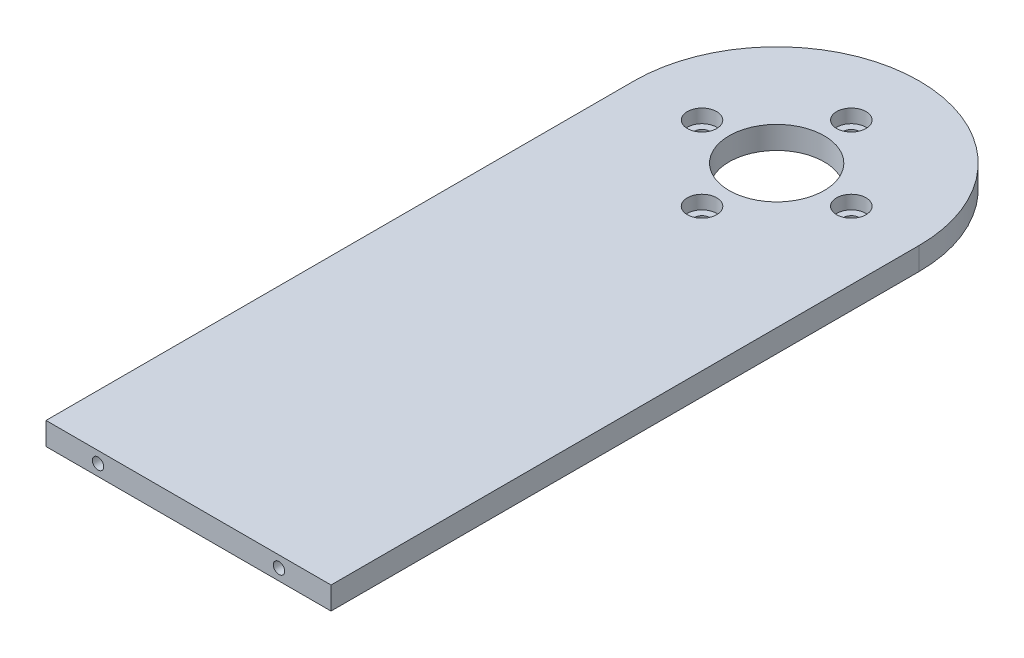
SolidWorks part; units mm, degrees
ref_plane "Front Plane" through (0, 0, 0) normal (0, 0, 1) x (1, 0, 0)
ref_plane "Top Plane" through (0, 0, 0) normal (0, 1, 0) x (1, 0, 0)
ref_plane "Right Plane" through (0, 0, 0) normal (1, 0, 0) x (0, 0, -1)
sketch "Sketch1" plane through (0, 0, 0) normal (0, 1, 0) x (1, 0, 0)
  line L1 (0, 0) -> (63, 0)
  line L2 (0, 0) -> (0, 130)
  line L4 (63, 0) -> (63, 130)
  arc A0 (0, 130) -> (63, 130) centre (31.5, 130) cw
  dimension "D3" = 130
  dimension "D4" = 31.5
  dimension "D1" = 130
  dimension "D2" = 63
extrude "Boss-Extrude1" add sketch "Sketch1" along normal blind 5 contours L2 A0 L4 L1
hole_wizard "M3x0.5 Tapped Hole1" positions "Sketch3" profile "Sketch2" tap size "M3x0.5" standard "ANSI Metric"
sketch "Sketch3" plane through (0, 0, 0) normal (0, 0, 1) x (1, 0, 0)
  line L0 (0, 2.5) -> (63, 2.5)
  line L1 (0, 5) -> (0, 0) construction
  line L2 (63, 5) -> (63, 0) construction
  line L3 (31.5, 5) -> (31.5, 0)
  line L4 (0, 5) -> (63, 5) construction
  line L5 (0, 0) -> (63, 0) construction
  point P9 (11.5, 2.5)
  point P11 (51.5, 2.5)
  dimension "D1" = 20
  dimension "D2" = 20
sketch "Sketch2" plane through (11.5, 2.5, 0) normal (1, 0, 0) x (0, -1, 0)
  line L0 (0, 0) -> (0, 8.2511)
  line L1 (0, 8.2511) -> (1.25, 7.5)
  line L2 (1.25, 7.5) -> (1.25, 0)
  line L5 (1.25, 0) -> (0, 0)
  line L10 (0, 8.2511) -> (-1.25, 7.5) construction
  line L11 (0, -6.35) -> (0, 107.95) construction
  dimension "Tap Drill Dia." = 2.5
  dimension "Tap Drill Depth" = 7.5
  dimension "Drill Angle" = 118
cosmetic thread "Hole Thread1" parameters "D1"=6, "D2"=3
cosmetic thread "Hole Thread2" parameters "D1"=6, "D2"=3
hole_wizard "CBORE for M3 SHCS1" positions "Sketch5" profile "Sketch4" counterbore size "M3" standard "ANSI Metric" end condition through all
sketch "Sketch5" plane through (0, 5, 0) normal (0, 1, 0) x (1, 0, 0)
  circle A5 centre (31.5, 130) radius 16.5
  arc A6 (63, 130) -> (0, 130) centre (31.5, 130) ccw construction
  point P53 (31.5, 113.5)
  point P57 (15, 130)
  point P58 (31.5, 113.5)
  point P62 (48, 130)
  point P67 (31.5, 161.5)
  point P73 (31.5, 146.5)
  dimension "D1" = 31.5
sketch "Sketch4" plane through (31.5, 5, -113.5) normal (1, 0, 0) x (0, 0, 1)
  line L0 (0, 0) -> (0, 5)
  line L1 (0, 5) -> (1.7, 5)
  line L3 (1.7, 5) -> (1.7, 3)
  line L4 (1.7, 3) -> (3.25, 3)
  line L5 (3.25, 3) -> (3.25, 0)
  line L7 (3.25, 0) -> (0, 0)
  line L11 (0, -6.35) -> (0, 107.95) construction
  dimension "Thru Hole Dia." = 3.4
  dimension "Thru Hole Depth" = 5
  dimension "C'Bore Dia." = 6.5
  dimension "C'Bore Depth" = 3
sketch "Sketch6" plane through (0, 5, 0) normal (0, 1, 0) x (1, 0, 0)
  line L0 (0, 0) -> (0, 130) construction
  circle A0 centre (31.5, 130) radius 10.5
  arc A1 (63, 130) -> (0, 130) centre (31.5, 130) ccw construction
  point P4 (31.5, 161.5)
  dimension "D1" = 31.5
  dimension "D3" = 21
  dimension "D2" = 31.5
extrude "Cut-Extrude1" cut sketch "Sketch6" against normal through all
